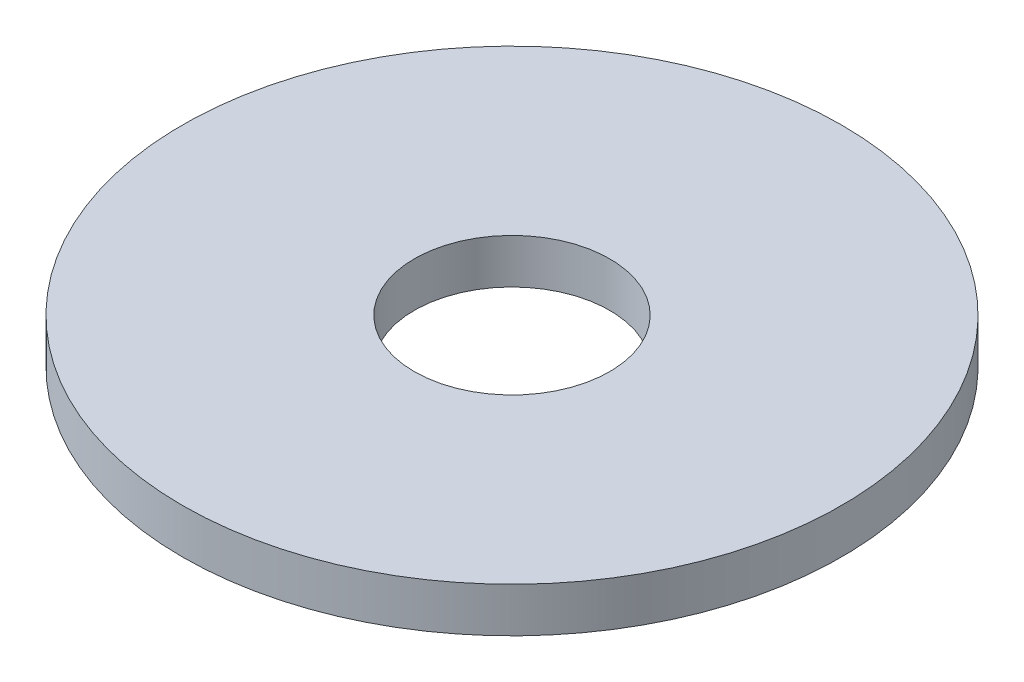
SolidWorks part; units mm, degrees
ref_plane "Alzado" through (0, 0, 0) normal (0, 0, 1) x (1, 0, 0)
ref_plane "Planta" through (0, 0, 0) normal (0, 1, 0) x (1, 0, 0)
ref_plane "Vista lateral" through (0, 0, 0) normal (1, 0, 0) x (0, 0, -1)
sketch "Croquis1" plane through (0, 0, 0) normal (0, 1, 0) x (1, 0, 0)
  circle A0 centre (0, 0) radius 5.9
  circle A1 centre (0, 0) radius 1.75
  dimension "D1" = 3.5
  dimension "D2" = 11.8
extrude "Saliente-Extruir1" add sketch "Croquis1" along normal blind 0.8
